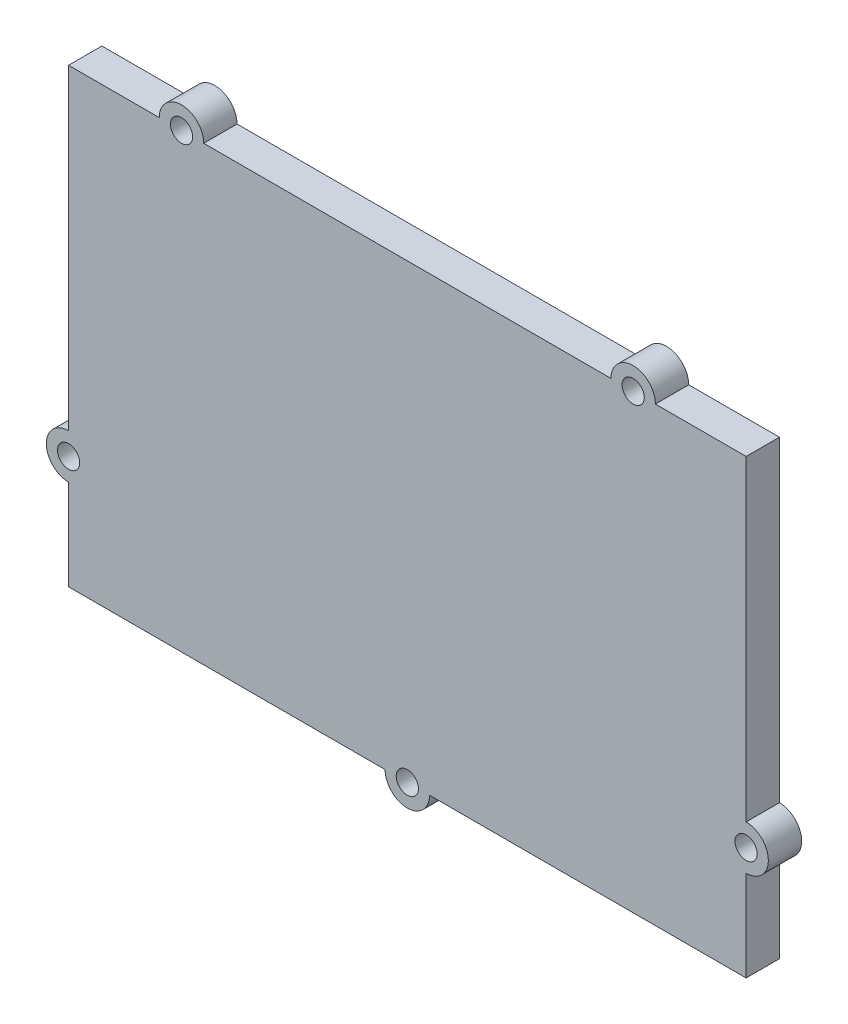
SolidWorks part; units mm, degrees
ref_plane "Plan de face" through (0, 0, 0) normal (0, 0, 1) x (1, 0, 0)
ref_plane "Plan de dessus" through (0, 0, 0) normal (0, 1, 0) x (1, 0, 0)
ref_plane "Plan de droite" through (0, 0, 0) normal (1, 0, 0) x (0, 0, -1)
sketch "Esquisse1" plane through (0, 0, 0) normal (0, 0, 1) x (1, 0, 0)
  line L0 (-21.32, 20.32) -> (-19.32, 20.32)
  line L1 (-30.48, -20.32) -> (-2, -20.32)
  line L2 (-30.48, -20.32) -> (-30.48, -12.16)
  line L3 (-30.48, 20.32) -> (-22.32, 20.32)
  line L4 (30.48, -20.32) -> (30.48, -12.16)
  line L5 (-30.48, -20.32) -> (30.48, 20.32) construction
  line L6 (-30.48, 20.32) -> (30.48, -20.32) construction
  line L7 (-18.32, 20.32) -> (18.32, 20.32)
  line L9 (22.32, 20.32) -> (30.48, 20.32)
  line L11 (30.48, -8.16) -> (30.48, 20.32)
  line L12 (2, -20.32) -> (30.48, -20.32)
  line L15 (-30.48, -8.16) -> (-30.48, 20.32)
  arc A0 (-18.32, 20.32) -> (-22.32, 20.32) centre (-20.32, 20.32) ccw
  arc A1 (22.32, 20.32) -> (18.32, 20.32) centre (20.32, 20.32) ccw
  arc A2 (-2, -20.32) -> (2, -20.32) centre (0, -20.32) ccw
  arc A3 (-30.48, -8.16) -> (-30.48, -12.16) centre (-30.48, -10.16) ccw
  arc A4 (30.48, -12.16) -> (30.48, -8.16) centre (30.48, -10.16) ccw
  circle A5 centre (-20.32, 20.32) radius 1
  circle A6 centre (20.32, 20.32) radius 1
  circle A7 centre (30.48, -10.16) radius 1
  circle A8 centre (0, -20.32) radius 1
  circle A9 centre (-30.48, -10.16) radius 1
  point P0 (0, 0)
  dimension "D3" = 4
  dimension "D4" = 4
  dimension "D5" = 4
  dimension "D6" = 4
  dimension "D7" = 4
  dimension "D12" = 2
  dimension "D13" = 2
  dimension "D14" = 2
  dimension "D15" = 2
  dimension "D16" = 2
  dimension "D1" = 40.64
  dimension "D2" = 60.96
  dimension "D8" = 10.16
  dimension "D9" = 10.16
  dimension "D10" = 10.16
  dimension "D11" = 10.16
  dimension "D17" = 30.48
extrude "Boss.-Extru.2" add sketch "Esquisse1" along normal blind 3 contours L4 A4 L11 L9 A1 L7 A0 L3 L15 A3 L2 L1 A2 L12 A9 A8 A7 A6 A5
equation "\"D4@Esquisse1\"=\"D3@Esquisse1\""
equation "\"D5@Esquisse1\"=\"D3@Esquisse1\""
equation "\"D6@Esquisse1\"=\"D3@Esquisse1\""
equation "\"D7@Esquisse1\"=\"D3@Esquisse1\""
equation "\"D13@Esquisse1\"=\"D12@Esquisse1\""
equation "\"D14@Esquisse1\"=\"D12@Esquisse1\""
equation "\"D15@Esquisse1\"=\"D12@Esquisse1\""
equation "\"D16@Esquisse1\"=\"D12@Esquisse1\""
